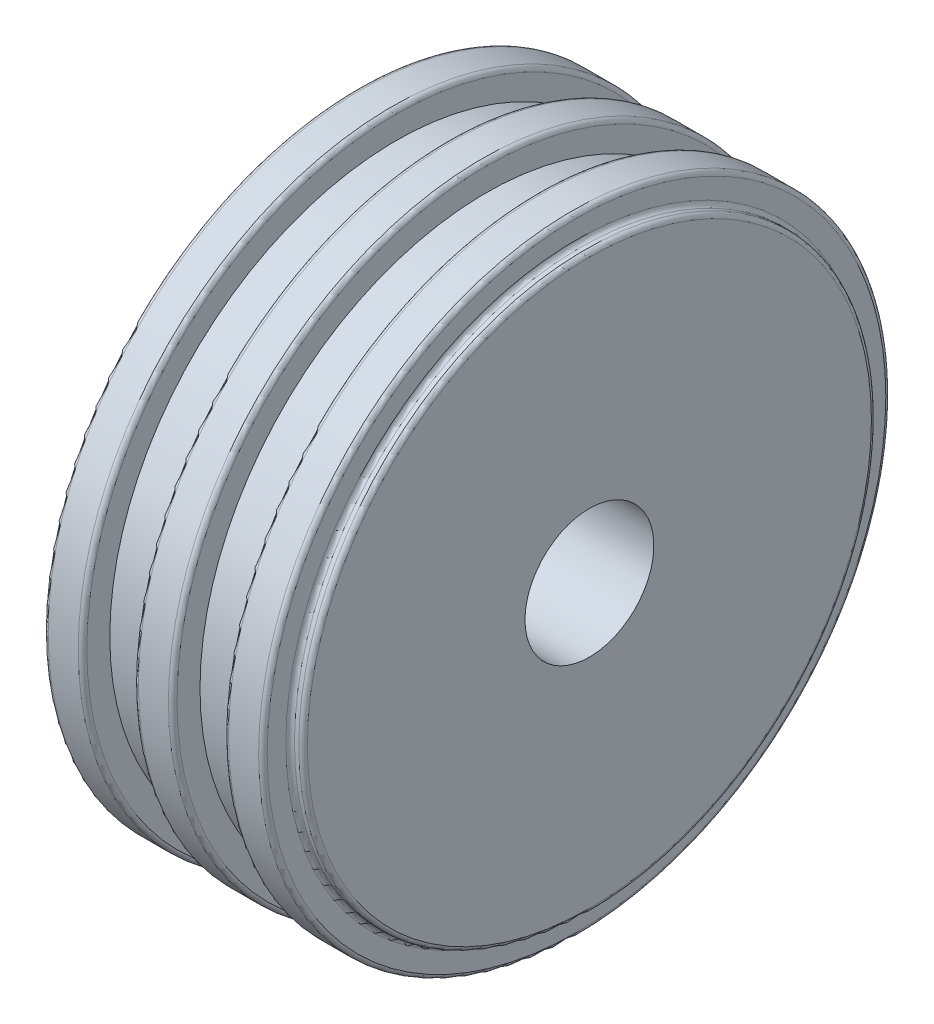
SolidWorks part; units mm, degrees
ref_plane "Front Plane" through (0, 0, 0) normal (0, 0, 1) x (1, 0, 0)
ref_plane "Top Plane" through (0, 0, 0) normal (0, 1, 0) x (1, 0, 0)
ref_plane "Right Plane" through (0, 0, 0) normal (1, 0, 0) x (0, 0, -1)
sketch "Sketch1" plane through (0, 0, 0) normal (0, 0, 1) x (1, 0, 0)
  line L0 (0, 0) -> (0, -220523.9051) construction
  line L1 (0, 0) -> (220523.9051, 0) construction
  line L2 (-3, 73.025) -> (-3, 66.675)
  line L3 (-3, 73.025) -> (-12, 73.025)
  line L4 (-12, 73.025) -> (-12, 66.675)
  line L5 (-12, 66.675) -> (-24, 66.675)
  line L6 (-24, 66.675) -> (-24, 73.025)
  line L7 (-24, 73.025) -> (-33, 73.025)
  line L8 (-33, 73.025) -> (-33, 66.675)
  line L9 (-33, 66.675) -> (-45, 66.675)
  line L10 (-45, 66.675) -> (-45, 73.025)
  line L11 (-45, 73.025) -> (-54, 73.025)
  line L12 (-54, 73.025) -> (-54, 66.675)
  line L13 (-54, 66.675) -> (-57, 66.675)
  line L14 (-57, 66.675) -> (-57, 15)
  line L15 (-57, 15) -> (0, 15)
  line L16 (-3, 66.675) -> (0, 66.675)
  line L17 (0, 66.675) -> (0, 15)
  dimension "D1" = 30
  dimension "D2" = 133.35
  dimension "D3" = 146.05
  dimension "D4" = 3
  dimension "D5" = 9
  dimension "D6" = 12
revolve "Revolve1" add sketch "Sketch1" angle 360 about L1
fillet "Fillet1" radius 1 10 edges at (-3, 0, 73.025) (-12, 0, 73.025) (-24, 0, 73.025) (-33, 0, 73.025) (-45, 0, 73.025) (-54, 0, 73.025) (0, 0, 66.675) (-3, 0, 66.675) (-54, 0, 66.675) (-57, 0, 66.675)
